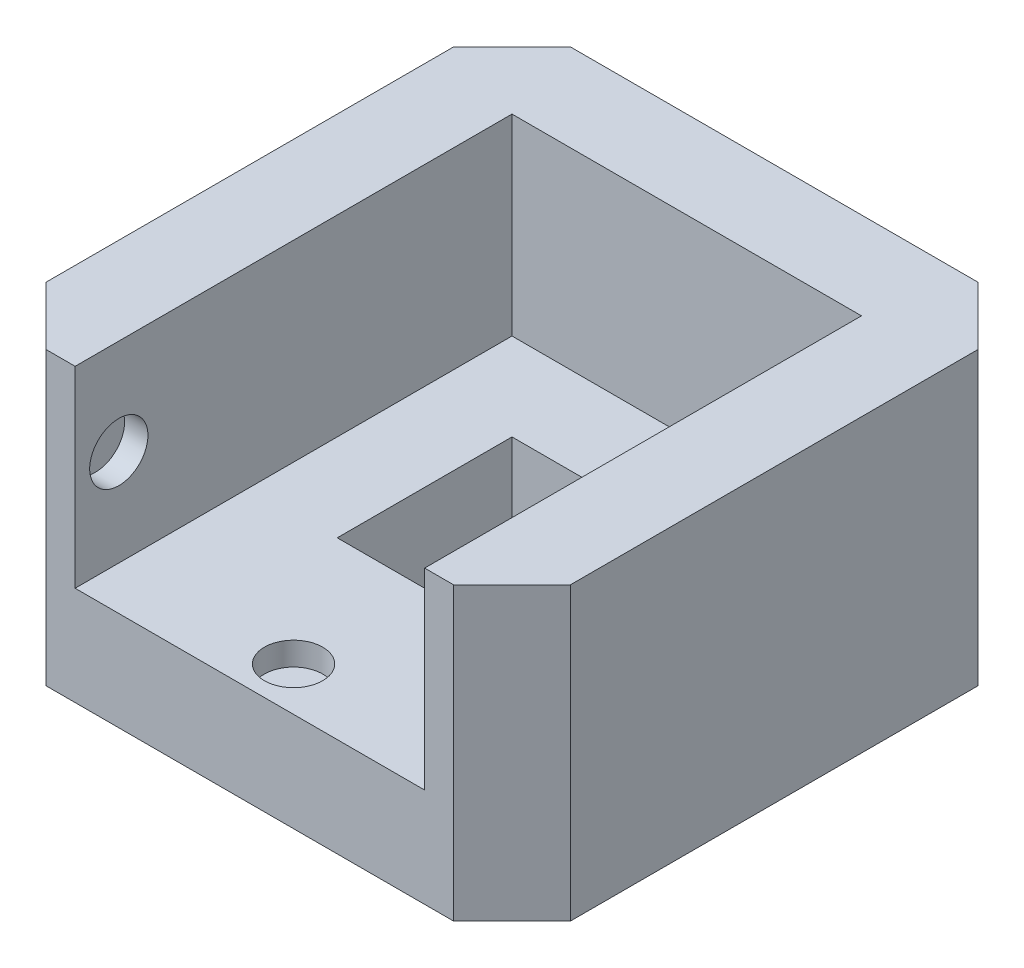
SolidWorks part; units mm, degrees
material "Polyurethane Foam Rigid"
ref_plane "Front Plane" through (0, 0, 0) normal (0, 0, 1) x (1, 0, 0)
ref_plane "Top Plane" through (0, 0, 0) normal (0, 1, 0) x (1, 0, 0)
ref_plane "Right Plane" through (0, 0, 0) normal (1, 0, 0) x (0, 0, -1)
sketch "Sketch1" plane through (0, 0, 0) normal (0, 1, 0) x (1, 0, 0)
  line L1 (-57.15, -57.15) -> (57.15, -57.15)
  line L2 (-57.15, -57.15) -> (-57.15, 57.15)
  line L3 (-57.15, 57.15) -> (57.15, 57.15)
  line L4 (57.15, -57.15) -> (57.15, 57.15)
  line L5 (-57.15, -57.15) -> (57.15, 57.15) construction
  line L6 (-57.15, 57.15) -> (57.15, -57.15) construction
  line L7 (-19.05, -19.05) -> (19.05, -19.05)
  line L8 (-19.05, -19.05) -> (-19.05, 19.05)
  line L9 (-19.05, 19.05) -> (19.05, 19.05)
  line L10 (19.05, -19.05) -> (19.05, 19.05)
  line L11 (-19.05, -19.05) -> (19.05, 19.05) construction
  line L12 (-19.05, 19.05) -> (19.05, -19.05) construction
  point P0 (0, 0)
  point P6 (0, 0)
  dimension "D1" = 114.3
  dimension "D2" = 114.3
  dimension "D3" = 38.1
  dimension "D4" = 38.1
extrude "Boss-Extrude1" add sketch "Sketch1" along normal blind 76.2
sketch "Sketch3" plane through (0, 76.2, 0) normal (0, 1, 0) x (1, 0, 0)
  line L1 (-38.1, -38.1) -> (38.1, -38.1)
  line L2 (-38.1, -38.1) -> (-38.1, 38.1)
  line L3 (-38.1, 38.1) -> (38.1, 38.1)
  line L4 (38.1, -38.1) -> (38.1, 38.1)
  line L5 (-38.1, -38.1) -> (38.1, 38.1) construction
  line L6 (-38.1, 38.1) -> (38.1, -38.1) construction
  point P0 (0, 0)
  dimension "D1" = 76.2
  dimension "D2" = 76.2
extrude "Cut-Extrude2" cut sketch "Sketch3" against normal blind 54.61
sketch "Sketch5" plane through (0, 76.2, 0) normal (0, 1, 0) x (1, 0, 0)
  line L1 (-38.1, -38.1) -> (38.1, -38.1)
  line L2 (-38.1, -38.1) -> (-38.1, 38.1)
  line L3 (-38.1, 38.1) -> (38.1, 38.1)
  line L4 (38.1, -38.1) -> (38.1, 38.1)
  line L5 (-38.1, -38.1) -> (38.1, 38.1) construction
  line L6 (-38.1, 38.1) -> (38.1, -38.1) construction
  line L7 (-57.15, -57.15) -> (57.15, -57.15)
  line L8 (-57.15, -57.15) -> (-57.15, 57.15)
  line L9 (-57.15, 57.15) -> (57.15, 57.15)
  line L10 (57.15, -57.15) -> (57.15, 57.15)
  line L11 (-57.15, -57.15) -> (57.15, 57.15) construction
  line L12 (-57.15, 57.15) -> (57.15, -57.15) construction
  point P0 (0, 0)
  point P7 (0, 0)
extrude "Cut-Extrude3" cut sketch "Sketch5" against normal blind 12.7
chamfer "Chamfer1" distance 12.7 angle 45 4 edges at (-57.15, 31.75, 57.15) (-57.15, 31.75, -57.15) (57.15, 31.75, -57.15) (57.15, 31.75, 57.15)
sketch "Sketch6" plane through (0, 0, 57.15) normal (0, 0, 1) x (1, 0, 0)
  line L0 (-44.45, 63.5) -> (44.45, 63.5) construction
  line L1 (-38.1, 63.5) -> (38.1, 63.5)
  line L2 (-38.1, 63.5) -> (-38.1, 21.59)
  line L3 (-38.1, 21.59) -> (38.1, 21.59)
  line L4 (38.1, 63.5) -> (38.1, 21.59)
  point P6 (0, 21.59)
  dimension "D1" = 41.91
  dimension "D2" = 76.2
extrude "Cut-Extrude4" cut sketch "Sketch6" against normal up to next
sketch "Sketch7" plane through (0, 21.59, 0) normal (0, 1, 0) x (1, 0, 0)
  line L0 (-57.15, -57.15) -> (57.15, -57.15) construction
  circle A0 centre (0, -47.625) radius 6.35
  point P2 (0, 0)
  dimension "D1" = 12.7
  dimension "D2" = 9.525
extrude "Cut-Extrude5" cut sketch "Sketch7" against normal blind 5.08
sketch "Sketch8" plane through (-38.1, 0, 0) normal (1, 0, 0) x (0, 0, -1)
  line L1 (-57.15, 63.5) -> (-57.15, 21.59) construction
  circle A0 centre (-47.625, 42.545) radius 6.35
  dimension "D1" = 12.7
  dimension "D2" = 9.525
sketch "Sketch9" plane through (38.1, 0, 0) normal (-1, 0, 0) x (0, 0, 1)
  circle A0 centre (47.625, 42.545) radius 6.35
  dimension "D1" = 12.7
extrude "Cut-Extrude6" cut sketch "Sketch9" against normal blind 5.08 contours A0
extrude "Cut-Extrude7" cut sketch "Sketch8" against normal blind 5.08 contours A0
